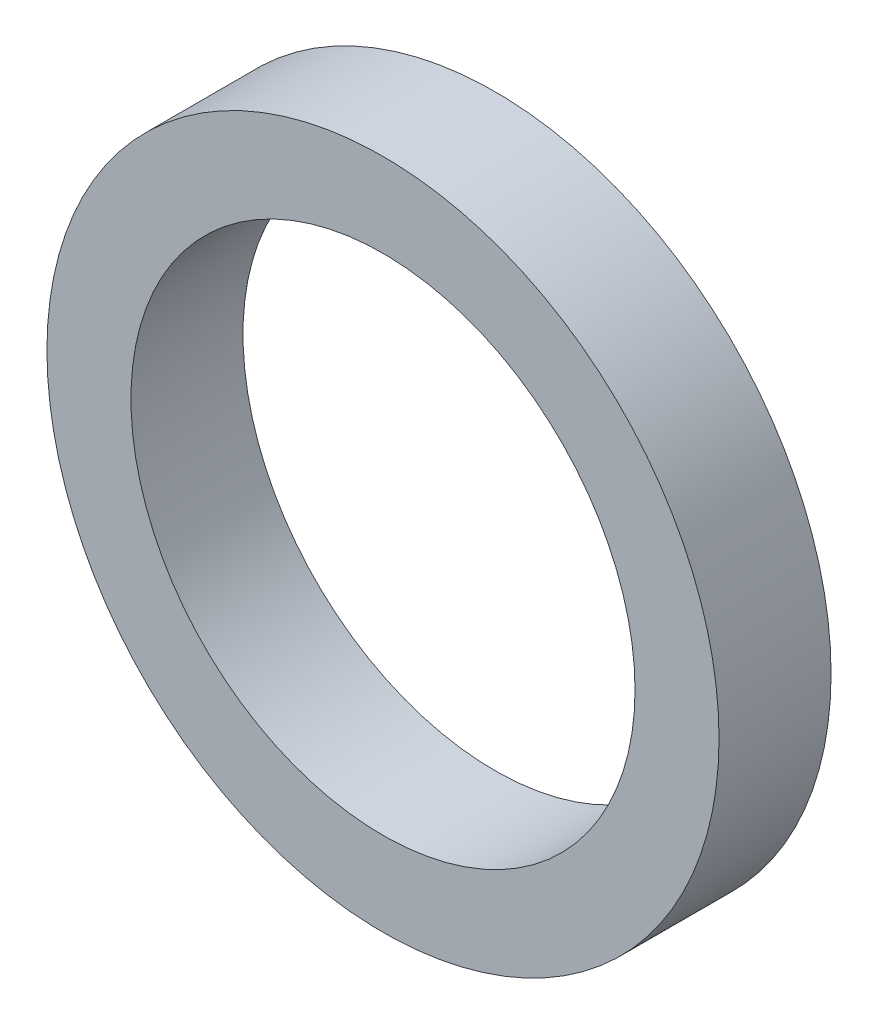
SolidWorks part; units mm, degrees
material "聚亚安酯(11671)"
ref_plane "前视基准面" through (0, 0, 0) normal (0, 0, 1) x (1, 0, 0)
ref_plane "上视基准面" through (0, 0, 0) normal (0, 1, 0) x (1, 0, 0)
ref_plane "右视基准面" through (0, 0, 0) normal (1, 0, 0) x (0, 0, -1)
sketch "草图1" plane through (0, 0, 0) normal (0, 0, 1) x (1, 0, 0)
  circle A0 centre (0, 0) radius 22.5
  circle A1 centre (0, 0) radius 30
  dimension "D1" = 45
  dimension "D2" = 60
extrude "凸台-拉伸1" add sketch "草图1" along normal blind 10
